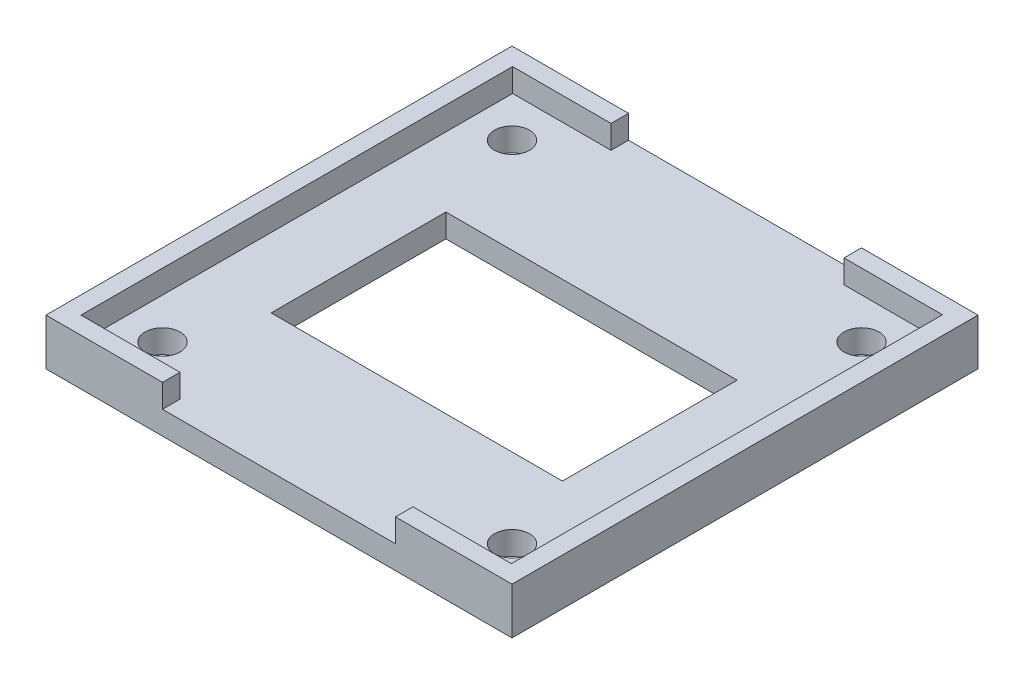
SolidWorks part; units mm, degrees
ref_plane "Front Plane" through (0, 0, 0) normal (0, 0, 1) x (1, 0, 0)
ref_plane "Top Plane" through (0, 0, 0) normal (0, 1, 0) x (1, 0, 0)
ref_plane "Right Plane" through (0, 0, 0) normal (1, 0, 0) x (0, 0, -1)
sketch "Sketch1" plane through (0, 0, 0) normal (0, 1, 0) x (1, 0, 0)
  line L0 (20, 0.6742) -> (-20, 0.6742) construction
  line L1 (-20, 20.6742) -> (20, 20.6742)
  line L2 (-20, 20.6742) -> (-20, -19.3258)
  line L3 (-20, -19.3258) -> (20, -19.3258)
  line L4 (20, 20.6742) -> (20, -19.3258)
  line L5 (0, 20.6742) -> (0, -19.3258) construction
  circle A0 centre (-15, 15.6742) radius 1.5
  circle A1 centre (15, 15.6742) radius 1.5
  circle A2 centre (15, -14.3258) radius 1.5
  circle A3 centre (-15, -14.3258) radius 1.5
  point P0 (0, 0)
  point P18 (20, 0.6742)
  dimension "D2" = 30
  dimension "D1" = 40
  dimension "D3" = 30
  dimension "D4" = 40
  dimension "D5" = 30
extrude "Boss-Extrude1" add sketch "Sketch1" along normal blind 2
sketch "Sketch2" plane through (0, 2, 0) normal (0, 1, 0) x (1, 0, 0)
  line L5 (-10, 19.1742) -> (-10, 20.6742)
  line L7 (-18.4998, -17.8258) -> (-18.4477, -17.8258)
  line L11 (20, 20.6742) -> (-20, 20.6742) construction
  line L13 (-10, 20.6742) -> (-20, 20.6742)
  line L15 (-20, 20.6742) -> (-20, -19.3258)
  line L17 (-20, -19.3258) -> (-10, -19.3258)
  line L19 (-20, -19.3258) -> (20, -19.3258) construction
  line L21 (-10, -19.3258) -> (-10, -17.8258)
  line L23 (-10, -17.8258) -> (-18.4477, -17.8258)
  line L27 (-18.4477, 19.1742) -> (-10, 19.1742)
  line L29 (0, 0) -> (0, -7.1761) construction
  line L30 (10, -19.3258) -> (10, -17.8258)
  line L31 (10, 19.1742) -> (10, 20.6742)
  line L32 (20, -19.3258) -> (10, -19.3258)
  line L33 (10, -17.8258) -> (18.4477, -17.8258)
  line L34 (10, 20.6742) -> (20, 20.6742)
  line L35 (18.4477, 19.1742) -> (10, 19.1742)
  line L37 (20, 20.6742) -> (20, -19.3258)
  line L38 (18.4477, -17.8258) -> (18.4477, 19.1742)
  line L40 (-18.4477, 19.1742) -> (-18.4998, -17.8258)
  point P0 (0, 0)
extrude "Boss-Extrude2" add sketch "Sketch2" along normal blind 2
sketch "Sketch3" plane through (0, 0, 0) normal (0, -1, 0) x (1, 0, 0)
  line L1 (-12.5, 7.5) -> (12.5, 7.5)
  line L2 (-12.5, 7.5) -> (-12.5, -7.5)
  line L3 (-12.5, -7.5) -> (12.5, -7.5)
  line L4 (12.5, 7.5) -> (12.5, -7.5)
  line L5 (-12.5, 7.5) -> (12.5, -7.5) construction
  line L6 (-12.5, -7.5) -> (12.5, 7.5) construction
  point P0 (0, 0)
  dimension "D1" = 25
  dimension "D2" = 15
extrude "Cut-Extrude1" cut sketch "Sketch3" against normal blind 2
